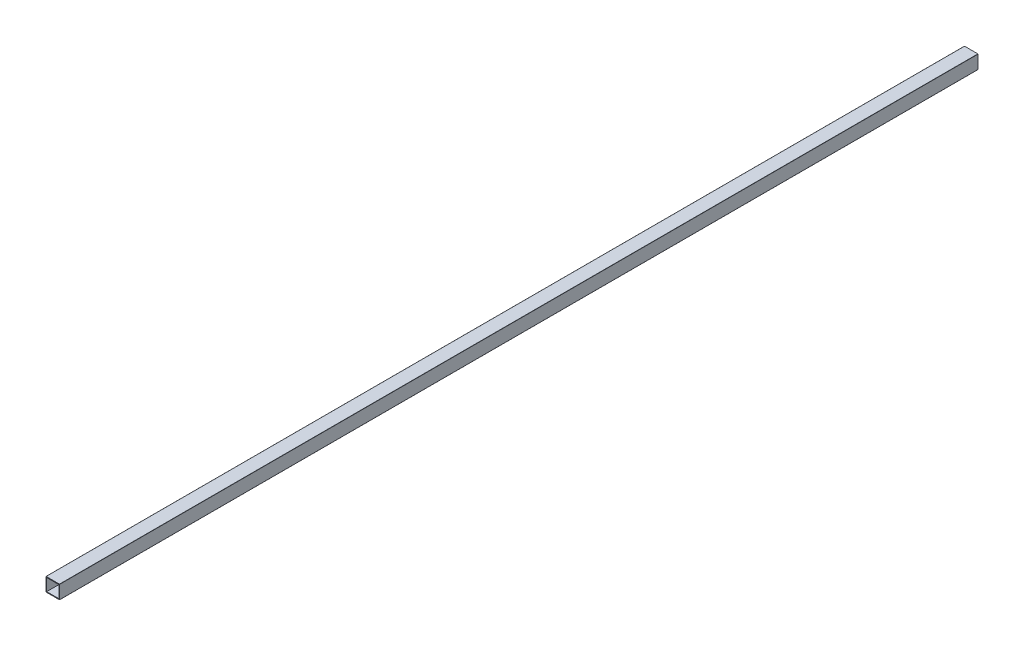
SolidWorks part; units mm, degrees
material "AISI 1035 Acero (SS)"
ref_plane "Alzado" through (0, 0, 0) normal (0, 0, 1) x (1, 0, 0)
ref_plane "Planta" through (0, 0, 0) normal (0, 1, 0) x (1, 0, 0)
ref_plane "Vista lateral" through (0, 0, 0) normal (1, 0, 0) x (0, 0, -1)
sketch "Croquis1" plane through (0, 0, 0) normal (0, 0, 1) x (1, 0, 0)
  line L0 (-39.9, -39.9) -> (-39.9, 39.9)
  line L1 (-43.45, -44.45) -> (43.45, -44.45)
  line L2 (-44.45, -43.45) -> (-44.45, 43.45)
  line L3 (-43.45, 44.45) -> (43.45, 44.45)
  line L4 (44.45, -43.45) -> (44.45, 43.45)
  line L5 (-44.45, -44.45) -> (44.45, 44.45) construction
  line L6 (-44.45, 44.45) -> (44.45, -44.45) construction
  line L7 (-39.9, 39.9) -> (39.9, 39.9)
  line L8 (39.9, -39.9) -> (39.9, 39.9)
  line L9 (-39.9, -39.9) -> (39.9, -39.9)
  line L10 (-44.45, 44.45) -> (44.45, 44.45) construction
  line L11 (44.45, -44.45) -> (44.45, 44.45) construction
  line L12 (-44.45, -44.45) -> (44.45, -44.45) construction
  line L13 (-44.45, -44.45) -> (-44.45, 44.45) construction
  arc A0 (43.45, 44.45) -> (44.45, 43.45) centre (43.45, 43.45) cw
  arc A1 (43.45, -44.45) -> (44.45, -43.45) centre (43.45, -43.45) ccw
  arc A2 (-43.45, -44.45) -> (-44.45, -43.45) centre (-43.45, -43.45) cw
  arc A3 (-44.45, 43.45) -> (-43.45, 44.45) centre (-43.45, 43.45) cw
  point P0 (0, 0)
  dimension "D2" = 1
  dimension "D1" = 88.9
  dimension "D3" = 4.55
extrude "Saliente-Extruir1" add sketch "Croquis1" along normal blind 6000
